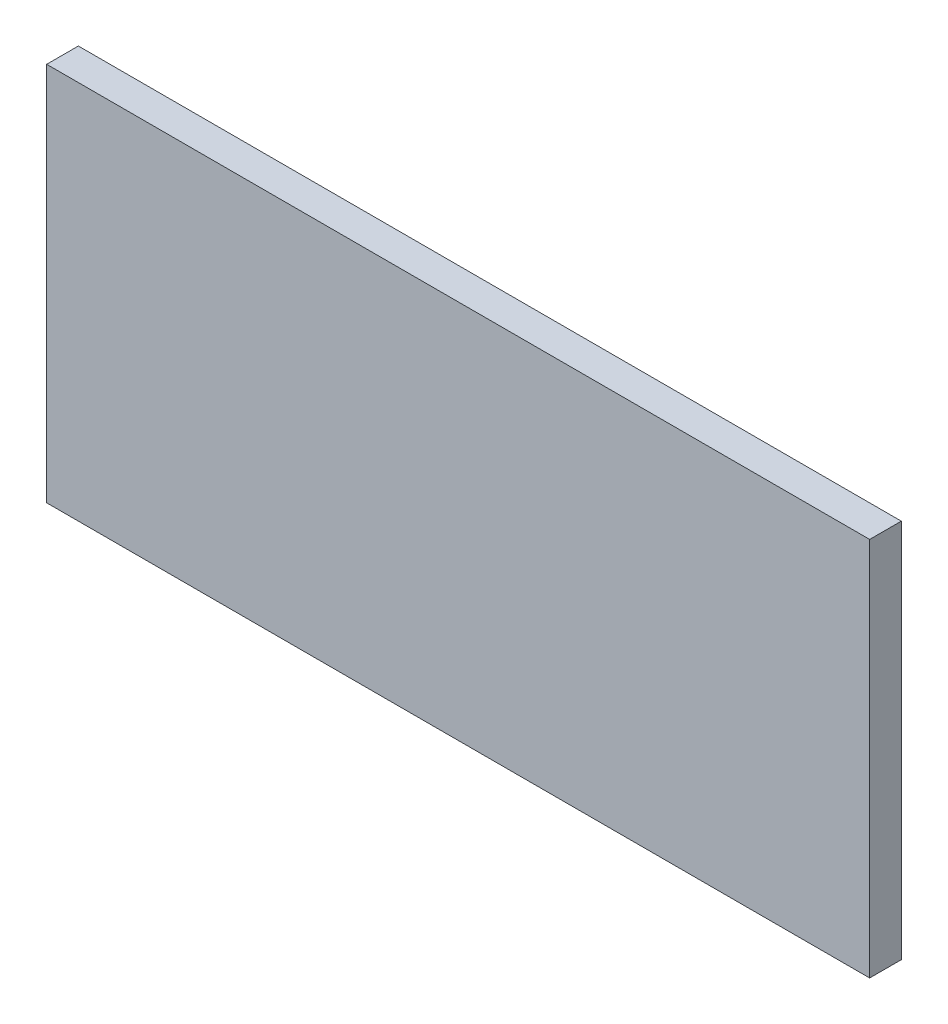
SolidWorks part; units mm, degrees
material "6061-T6 (SS)"
ref_plane "Front Plane" through (0, 0, 0) normal (0, 0, 1) x (1, 0, 0)
ref_plane "Top Plane" through (0, 0, 0) normal (0, 1, 0) x (1, 0, 0)
ref_plane "Right Plane" through (0, 0, 0) normal (1, 0, 0) x (0, 0, -1)
sketch "Sketch1" plane through (0, 0, 0) normal (0, 0, 1) x (1, 0, 0)
  line L0 (-67.913, 0) -> (67.913, 0) construction
  line L1 (0, -48.4895) -> (0, 48.4895) construction
  line L3 (-41.275, -19.05) -> (41.275, -19.05)
  line L4 (-41.275, -19.05) -> (-41.275, 19.05)
  line L5 (-41.275, 19.05) -> (41.275, 19.05)
  line L6 (41.275, -19.05) -> (41.275, 19.05)
  line L7 (-41.275, -19.05) -> (41.275, 19.05) construction
  line L8 (-41.275, 19.05) -> (41.275, -19.05) construction
  point P0 (0, 0)
  point P4 (0, 0)
  point P8 (0, 0)
  dimension "D1" = 82.55
  dimension "D2" = 38.1
extrude "Boss-Extrude1" add sketch "Sketch1" along normal blind 3.175
